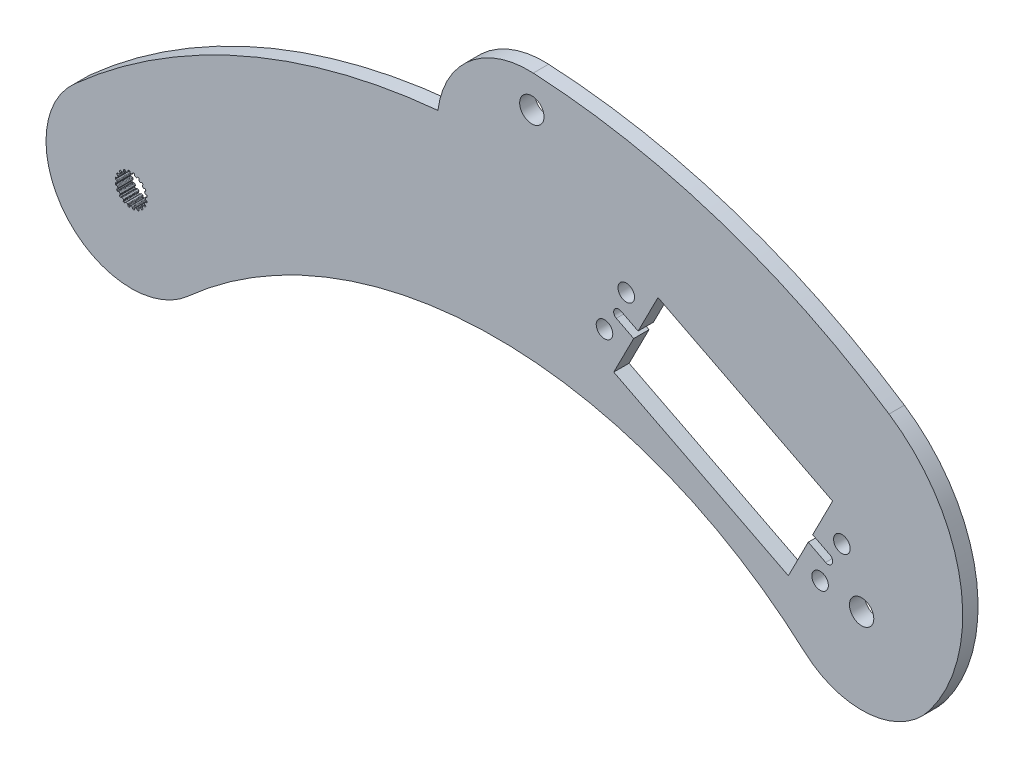
SolidWorks part; units mm, degrees
ref_plane "Front Plane" through (0, 0, 0) normal (0, 0, 1) x (1, 0, 0)
ref_plane "Top Plane" through (0, 0, 0) normal (0, 1, 0) x (1, 0, 0)
ref_plane "Right Plane" through (0, 0, 0) normal (1, 0, 0) x (0, 0, -1)
sketch "Sketch1" plane through (0, 0, 0) normal (0, 0, 1) x (1, 0, 0)
  line L0 (-0.1069, 2.9699) -> (0.1069, 2.9699)
  line L1 (0.3159, 3.2375) -> (0.2537, 3.0575)
  line L2 (-0.2964, 3.2367) -> (-0.2318, 3.0575)
  line L3 (-0.2964, 3.2367) -> (0.3159, 3.2375) construction
  line L4 (0, 3.3252) -> (0, 0) construction
  line L5 (-0.2318, 3.0575) -> (0.2537, 3.0575) construction
  line L6 (-0.4281, 3.3241) -> (0.4281, 3.3263) construction
  line L7 (0.7183, 3.1698) -> (0.7244, 2.9795)
  line L8 (0.816, 2.8576) -> (1.0195, 2.7915)
  line L9 (1.3009, 2.9815) -> (1.1862, 2.8295)
  line L10 (1.6627, 2.7927) -> (1.6097, 2.6099)
  line L11 (1.6591, 2.4655) -> (1.8322, 2.3398)
  line L12 (2.1585, 2.4335) -> (2.0025, 2.3245)
  line L13 (2.4443, 2.1423) -> (2.3374, 1.9847)
  line L14 (2.3398, 1.8322) -> (2.4655, 1.6591)
  line L15 (2.8049, 1.6474) -> (2.6228, 1.5919)
  line L16 (2.9866, 1.2821) -> (2.8363, 1.1653)
  line L17 (2.7915, 1.0195) -> (2.8576, 0.816)
  line L18 (3.1767, 0.7) -> (2.9863, 0.7035)
  line L19 (3.2367, 0.2964) -> (3.0575, 0.2318)
  line L20 (2.9699, 0.1069) -> (2.9699, -0.1069)
  line L21 (3.2375, -0.3159) -> (3.0575, -0.2537)
  line L22 (3.1698, -0.7183) -> (2.9795, -0.7244)
  line L23 (2.8576, -0.816) -> (2.7915, -1.0195)
  line L24 (2.9815, -1.3009) -> (2.8295, -1.1862)
  line L25 (2.7927, -1.6627) -> (2.6099, -1.6097)
  line L26 (2.4655, -1.6591) -> (2.3398, -1.8322)
  line L27 (2.4335, -2.1585) -> (2.3245, -2.0025)
  line L28 (2.1423, -2.4443) -> (1.9847, -2.3374)
  line L29 (1.8322, -2.3398) -> (1.6591, -2.4655)
  line L30 (1.6474, -2.8049) -> (1.5919, -2.6228)
  line L31 (1.2821, -2.9866) -> (1.1653, -2.8363)
  line L32 (1.0195, -2.7915) -> (0.816, -2.8576)
  line L33 (0.7, -3.1767) -> (0.7035, -2.9863)
  line L34 (0.2964, -3.2367) -> (0.2318, -3.0575)
  line L35 (0.1069, -2.9699) -> (-0.1069, -2.9699)
  line L36 (-0.3159, -3.2375) -> (-0.2537, -3.0575)
  line L37 (-0.7183, -3.1698) -> (-0.7244, -2.9795)
  line L38 (-0.816, -2.8576) -> (-1.0195, -2.7915)
  line L39 (-1.3009, -2.9815) -> (-1.1862, -2.8295)
  line L40 (-1.6627, -2.7927) -> (-1.6097, -2.6099)
  line L41 (-1.6591, -2.4655) -> (-1.8322, -2.3398)
  line L42 (-2.1585, -2.4335) -> (-2.0025, -2.3245)
  line L43 (-2.4443, -2.1423) -> (-2.3374, -1.9847)
  line L44 (-2.3398, -1.8322) -> (-2.4655, -1.6591)
  line L45 (-2.8049, -1.6474) -> (-2.6228, -1.5919)
  line L46 (-2.9866, -1.2821) -> (-2.8363, -1.1653)
  line L47 (-2.7915, -1.0195) -> (-2.8576, -0.816)
  line L48 (-3.1767, -0.7) -> (-2.9863, -0.7035)
  line L49 (-3.2367, -0.2964) -> (-3.0575, -0.2318)
  line L50 (-2.9699, -0.1069) -> (-2.9699, 0.1069)
  line L51 (-3.2375, 0.3159) -> (-3.0575, 0.2537)
  line L52 (-3.1698, 0.7183) -> (-2.9795, 0.7244)
  line L53 (-2.8576, 0.816) -> (-2.7915, 1.0195)
  line L54 (-2.9815, 1.3009) -> (-2.8295, 1.1862)
  line L55 (-2.7927, 1.6627) -> (-2.6099, 1.6097)
  line L56 (-2.4655, 1.6591) -> (-2.3398, 1.8322)
  line L57 (-2.4335, 2.1585) -> (-2.3245, 2.0025)
  line L58 (-2.1423, 2.4443) -> (-1.9847, 2.3374)
  line L59 (-1.8322, 2.3398) -> (-1.6591, 2.4655)
  line L60 (-1.6474, 2.8049) -> (-1.5919, 2.6228)
  line L61 (-1.2821, 2.9866) -> (-1.1653, 2.8363)
  line L62 (-1.0195, 2.7915) -> (-0.816, 2.8576)
  line L63 (-0.7, 3.1767) -> (-0.7035, 2.9863)
  line L64 (0.4281, 3.3263) -> (0.62, 3.2938)
  line L65 (1.4351, 3.0312) -> (1.6075, 2.9409)
  line L66 (2.3015, 2.4394) -> (2.4376, 2.3003)
  line L67 (2.9427, 1.6088) -> (3.0291, 1.4344)
  line L68 (3.2958, 0.6207) -> (3.3241, 0.4281)
  line L69 (3.3263, -0.4281) -> (3.2938, -0.62)
  line L70 (3.0312, -1.4351) -> (2.9409, -1.6075)
  line L71 (2.4394, -2.3015) -> (2.3003, -2.4376)
  line L72 (1.6088, -2.9427) -> (1.4344, -3.0291)
  line L73 (0.6207, -3.2958) -> (0.4281, -3.3241)
  line L74 (-0.4281, -3.3263) -> (-0.62, -3.2938)
  line L75 (-1.4351, -3.0312) -> (-1.6075, -2.9409)
  line L76 (-2.3015, -2.4394) -> (-2.4376, -2.3003)
  line L77 (-2.9427, -1.6088) -> (-3.0291, -1.4344)
  line L78 (-3.2958, -0.6207) -> (-3.3241, -0.4281)
  line L79 (-3.3263, 0.4281) -> (-3.2938, 0.62)
  line L80 (-3.0312, 1.4351) -> (-2.9409, 1.6075)
  line L81 (-2.4394, 2.3015) -> (-2.3003, 2.4376)
  line L82 (-1.6088, 2.9427) -> (-1.4344, 3.0291)
  line L83 (-0.6207, 3.2958) -> (-0.4281, 3.3241)
  line L84 (-11.8753, 13.2369) -> (11.8753, -13.2369) construction
  line L85 (164.2753, 13.2369) -> (140.5247, -13.2369) construction
  line L86 (0, 0) -> (152.4, 0) construction
  arc A0 (0.2537, 3.0575) -> (0.1069, 2.9699) centre (0.1283, 3.1009) cw
  arc A1 (-0.2318, 3.0575) -> (-0.1069, 2.9699) centre (-0.1069, 3.1026) ccw
  arc A2 (0.62, 3.2938) -> (0.7183, 3.1698) centre (0.5856, 3.1656) cw
  arc A3 (0.7244, 2.9795) -> (0.816, 2.8576) centre (0.857, 2.9838) ccw
  arc A4 (-0.4281, 3.3241) -> (-0.2964, 3.2367) centre (-0.4213, 3.1916) cw
  arc A5 (0.4281, 3.3263) -> (0.3159, 3.2375) centre (0.4413, 3.1942) ccw
  arc A6 (1.1862, 2.8295) -> (1.0195, 2.7915) centre (1.0802, 2.9095) cw
  arc A7 (1.4351, 3.0312) -> (1.3009, 2.9815) centre (1.4068, 2.9015) ccw
  arc A8 (1.6075, 2.9409) -> (1.6627, 2.7927) centre (1.5352, 2.8297) cw
  arc A9 (1.6097, 2.6099) -> (1.6591, 2.4655) centre (1.7371, 2.5729) ccw
  arc A10 (2.0025, 2.3245) -> (1.8322, 2.3398) centre (1.9264, 2.4332) cw
  arc A11 (2.3015, 2.4394) -> (2.1585, 2.4335) centre (2.2346, 2.3248) ccw
  arc A12 (2.4376, 2.3003) -> (2.4443, 2.1423) centre (2.3345, 2.2168) cw
  arc A13 (2.3374, 1.9847) -> (2.3398, 1.8322) centre (2.4472, 1.9102) ccw
  arc A14 (2.6228, 1.5919) -> (2.4655, 1.6591) centre (2.5841, 1.7189) cw
  arc A15 (2.9427, 1.6088) -> (2.8049, 1.6474) centre (2.8436, 1.5205) ccw
  arc A16 (3.0291, 1.4344) -> (2.9866, 1.2821) centre (2.9052, 1.3869) cw
  arc A17 (2.8363, 1.1653) -> (2.7915, 1.0195) centre (2.9177, 1.0605) ccw
  arc A18 (2.9863, 0.7035) -> (2.8576, 0.816) centre (2.9887, 0.8362) cw
  arc A19 (3.2958, 0.6207) -> (3.1767, 0.7) centre (3.1743, 0.5673) ccw
  arc A20 (3.3241, 0.4281) -> (3.2367, 0.2964) centre (3.1916, 0.4213) cw
  arc A21 (3.0575, 0.2318) -> (2.9699, 0.1069) centre (3.1026, 0.1069) ccw
  arc A22 (3.0575, -0.2537) -> (2.9699, -0.1069) centre (3.1009, -0.1283) cw
  arc A23 (3.3263, -0.4281) -> (3.2375, -0.3159) centre (3.1942, -0.4413) ccw
  arc A24 (3.2938, -0.62) -> (3.1698, -0.7183) centre (3.1656, -0.5856) cw
  arc A25 (2.9795, -0.7244) -> (2.8576, -0.816) centre (2.9838, -0.857) ccw
  arc A26 (2.8295, -1.1862) -> (2.7915, -1.0195) centre (2.9095, -1.0802) cw
  arc A27 (3.0312, -1.4351) -> (2.9815, -1.3009) centre (2.9015, -1.4068) ccw
  arc A28 (2.9409, -1.6075) -> (2.7927, -1.6627) centre (2.8297, -1.5352) cw
  arc A29 (2.6099, -1.6097) -> (2.4655, -1.6591) centre (2.5729, -1.7371) ccw
  arc A30 (2.3245, -2.0025) -> (2.3398, -1.8322) centre (2.4332, -1.9264) cw
  arc A31 (2.4394, -2.3015) -> (2.4335, -2.1585) centre (2.3248, -2.2346) ccw
  arc A32 (2.3003, -2.4376) -> (2.1423, -2.4443) centre (2.2168, -2.3345) cw
  arc A33 (1.9847, -2.3374) -> (1.8322, -2.3398) centre (1.9102, -2.4472) ccw
  arc A34 (1.5919, -2.6228) -> (1.6591, -2.4655) centre (1.7189, -2.5841) cw
  arc A35 (1.6088, -2.9427) -> (1.6474, -2.8049) centre (1.5205, -2.8436) ccw
  arc A36 (1.4344, -3.0291) -> (1.2821, -2.9866) centre (1.3869, -2.9052) cw
  arc A37 (1.1653, -2.8363) -> (1.0195, -2.7915) centre (1.0605, -2.9177) ccw
  arc A38 (0.7035, -2.9863) -> (0.816, -2.8576) centre (0.8362, -2.9887) cw
  arc A39 (0.6207, -3.2958) -> (0.7, -3.1767) centre (0.5673, -3.1743) ccw
  arc A40 (0.4281, -3.3241) -> (0.2964, -3.2367) centre (0.4213, -3.1916) cw
  arc A41 (0.2318, -3.0575) -> (0.1069, -2.9699) centre (0.1069, -3.1026) ccw
  arc A42 (-0.2537, -3.0575) -> (-0.1069, -2.9699) centre (-0.1283, -3.1009) cw
  arc A43 (-0.4281, -3.3263) -> (-0.3159, -3.2375) centre (-0.4413, -3.1942) ccw
  arc A44 (-0.62, -3.2938) -> (-0.7183, -3.1698) centre (-0.5856, -3.1656) cw
  arc A45 (-0.7244, -2.9795) -> (-0.816, -2.8576) centre (-0.857, -2.9838) ccw
  arc A46 (-1.1862, -2.8295) -> (-1.0195, -2.7915) centre (-1.0802, -2.9095) cw
  arc A47 (-1.4351, -3.0312) -> (-1.3009, -2.9815) centre (-1.4068, -2.9015) ccw
  arc A48 (-1.6075, -2.9409) -> (-1.6627, -2.7927) centre (-1.5352, -2.8297) cw
  arc A49 (-1.6097, -2.6099) -> (-1.6591, -2.4655) centre (-1.7371, -2.5729) ccw
  arc A50 (-2.0025, -2.3245) -> (-1.8322, -2.3398) centre (-1.9264, -2.4332) cw
  arc A51 (-2.3015, -2.4394) -> (-2.1585, -2.4335) centre (-2.2346, -2.3248) ccw
  arc A52 (-2.4376, -2.3003) -> (-2.4443, -2.1423) centre (-2.3345, -2.2168) cw
  arc A53 (-2.3374, -1.9847) -> (-2.3398, -1.8322) centre (-2.4472, -1.9102) ccw
  arc A54 (-2.6228, -1.5919) -> (-2.4655, -1.6591) centre (-2.5841, -1.7189) cw
  arc A55 (-2.9427, -1.6088) -> (-2.8049, -1.6474) centre (-2.8436, -1.5205) ccw
  arc A56 (-3.0291, -1.4344) -> (-2.9866, -1.2821) centre (-2.9052, -1.3869) cw
  arc A57 (-2.8363, -1.1653) -> (-2.7915, -1.0195) centre (-2.9177, -1.0605) ccw
  arc A58 (-2.9863, -0.7035) -> (-2.8576, -0.816) centre (-2.9887, -0.8362) cw
  arc A59 (-3.2958, -0.6207) -> (-3.1767, -0.7) centre (-3.1743, -0.5673) ccw
  arc A60 (-3.3241, -0.4281) -> (-3.2367, -0.2964) centre (-3.1916, -0.4213) cw
  arc A61 (-3.0575, -0.2318) -> (-2.9699, -0.1069) centre (-3.1026, -0.1069) ccw
  arc A62 (-3.0575, 0.2537) -> (-2.9699, 0.1069) centre (-3.1009, 0.1283) cw
  arc A63 (-3.3263, 0.4281) -> (-3.2375, 0.3159) centre (-3.1942, 0.4413) ccw
  arc A64 (-3.2938, 0.62) -> (-3.1698, 0.7183) centre (-3.1656, 0.5856) cw
  arc A65 (-2.9795, 0.7244) -> (-2.8576, 0.816) centre (-2.9838, 0.857) ccw
  arc A66 (-2.8295, 1.1862) -> (-2.7915, 1.0195) centre (-2.9095, 1.0802) cw
  arc A67 (-3.0312, 1.4351) -> (-2.9815, 1.3009) centre (-2.9015, 1.4068) ccw
  arc A68 (-2.9409, 1.6075) -> (-2.7927, 1.6627) centre (-2.8297, 1.5352) cw
  arc A69 (-2.6099, 1.6097) -> (-2.4655, 1.6591) centre (-2.5729, 1.7371) ccw
  arc A70 (-2.3245, 2.0025) -> (-2.3398, 1.8322) centre (-2.4332, 1.9264) cw
  arc A71 (-2.4394, 2.3015) -> (-2.4335, 2.1585) centre (-2.3248, 2.2346) ccw
  arc A72 (-2.3003, 2.4376) -> (-2.1423, 2.4443) centre (-2.2168, 2.3345) cw
  arc A73 (-1.9847, 2.3374) -> (-1.8322, 2.3398) centre (-1.9102, 2.4472) ccw
  arc A74 (-1.5919, 2.6228) -> (-1.6591, 2.4655) centre (-1.7189, 2.5841) cw
  arc A75 (-1.6088, 2.9427) -> (-1.6474, 2.8049) centre (-1.5205, 2.8436) ccw
  arc A76 (-1.4344, 3.0291) -> (-1.2821, 2.9866) centre (-1.3869, 2.9052) cw
  arc A77 (-1.1653, 2.8363) -> (-1.0195, 2.7915) centre (-1.0605, 2.9177) ccw
  arc A78 (-0.7035, 2.9863) -> (-0.816, 2.8576) centre (-0.8362, 2.9887) cw
  arc A79 (-0.6207, 3.2958) -> (-0.7, 3.1767) centre (-0.5673, 3.1743) ccw
  circle A80 centre (0, 0) radius 12.7 construction
  arc A81 (-11.8753, 13.2369) -> (164.2753, 13.2369) centre (76.2, -84.9368) cw
  arc A82 (11.8753, -13.2369) -> (140.5247, -13.2369) centre (76.2, -84.9368) cw
  arc A84 (-11.8753, 13.2369) -> (11.8753, -13.2369) centre (0, 0) ccw
  arc A85 (164.2753, 13.2369) -> (140.5247, -13.2369) centre (152.4, 0) cw
  point P14 (0, 2.9699)
  point P26 (0, 0)
  point P247 (0, 0)
  dimension "D4" = 0.1327
  dimension "D8" = 20
  dimension "D9" = 25.4
  dimension "D10" = 131.8914
  dimension "D1" = 2.9699
  dimension "D2" = 0.2139
  dimension "D3" = 0.1904
  dimension "D5" = 0.0877
  dimension "D6" = 0.4855
  dimension "D7" = 0.8563
  dimension "D11" = 35.5662
  dimension "D12" = 152.4
extrude "Boss-Extrude1" add sketch "Sketch1" along normal blind 3.2004
sketch "Sketch2" plane through (0, 0, 3.2004) normal (0, 0, 1) x (1, 0, 0)
  line L0 (132.2879, 12.7254) -> (132.9641, 14.0508) construction
  line L5 (128.1311, 26.252) -> (118.8966, 8.1515) construction
  line L7 (109.9175, 35.5442) -> (146.3447, 16.9598)
  line L13 (109.9175, 35.5442) -> (100.683, 17.4437)
  line L19 (98.7496, 24.2228) -> (103.2942, 33.1305) construction
  line L20 (143.7335, 1.273) -> (148.2781, 10.1807) construction
  line L24 (101.0219, 28.6767) -> (146.0058, 5.7268) construction
  line L30 (100.683, 17.4437) -> (137.1102, -1.1407)
  line L31 (146.3447, 16.9598) -> (137.1102, -1.1407)
  circle A7 centre (103.2942, 33.1305) radius 1.7272
  circle A9 centre (143.7335, 1.273) radius 1.7272
  circle A10 centre (148.2781, 10.1807) radius 1.7272
  circle A11 centre (98.7496, 24.2228) radius 1.7272
  circle A13 centre (132.2879, 12.7254) radius 3.429 construction
  arc A14 (0, 0) -> (152.4, 0) centre (76.2, -84.9368) cw construction
  arc A15 (-11.8753, 13.2369) -> (11.8753, -13.2369) centre (0, 0) ccw construction
  arc A16 (140.5247, -13.2369) -> (164.2753, 13.2369) centre (152.4, 0) ccw construction
  arc A17 (164.2753, 13.2369) -> (-11.8753, 13.2369) centre (76.2, -84.9368) ccw construction
  circle A18 centre (152.4, 0) radius 2.54
  point P0 (132.2879, 12.7254)
  point P1 (99.9946, 26.663)
  point P24 (123.5139, 17.2018)
  dimension "D2" = 15.4
  dimension "D3" = 6.858
  dimension "D5" = 3.4544
  dimension "D10" = 5.08
  dimension "D6" = 2.2606
  dimension "D8" = 20.32
  dimension "D13" = 23.7998
  dimension "D1" = 50.5
  dimension "D4" = 10
  dimension "D7" = 1.4879
  dimension "D9" = 40.894
extrude "Cut-Extrude1" cut sketch "Sketch2" against normal up to surface (3.2004 mm away) up to face at (76.2, 8.6481, 0)
sketch "Sketch3" plane through (0, 0, 3.2004) normal (0, 0, 1) x (1, 0, 0)
  line L0 (146.3447, 16.9598) -> (137.1102, -1.1407) construction
  line L1 (109.9175, 35.5442) -> (100.683, 17.4437) construction
  line L4 (102.1419, 29.2459) -> (105.762, 27.399)
  line L5 (102.1419, 29.2459) -> (101.2184, 27.4358) construction
  line L7 (101.2184, 27.4358) -> (104.8385, 25.5889)
  line L8 (105.762, 27.399) -> (104.8385, 25.5889)
  line L9 (142.1892, 8.8146) -> (145.8093, 6.9677)
  line L10 (142.1892, 8.8146) -> (141.2657, 7.0045)
  line L11 (141.2657, 7.0045) -> (144.8858, 5.1576)
  line L12 (145.8093, 6.9677) -> (144.8858, 5.1576) construction
  arc A6 (145.8093, 6.9677) -> (144.8858, 5.1576) centre (145.3475, 6.0627) cw
  arc A7 (102.1419, 29.2459) -> (101.2184, 27.4358) centre (101.6802, 28.3409) ccw
  point P22 (105.3003, 26.494)
  point P23 (141.7274, 7.9096)
  dimension "D4" = 4.064
  dimension "D5" = 2.032
extrude "Cut-Extrude2" cut sketch "Sketch3" against normal up to surface (3.2004 mm away) up to face at (97.0224, 24.2228, 0)
sketch "Sketch4" plane through (0, 0, 3.2004) normal (0, 0, 1) x (1, 0, 0)
  line L1 (83.5881, 56.2861) -> (152.4, 0) construction
  line L2 (83.5881, 56.2861) -> (83.1655, 46.7705) construction
  line L4 (158.1231, 38.5869) -> (166.6312, -10.6636) construction
  line L5 (83.89, 63.0847) -> (63.9945, 46.3886) construction
  arc A0 (63.9945, 46.3886) -> (83.89, 63.0847) centre (82.9016, 44.0604) cw
  arc A1 (164.2753, 13.2369) -> (-11.8753, 13.2369) centre (76.2, -84.9368) ccw construction
  circle A3 centre (152.4, 0) radius 2.54 construction
  circle A4 centre (83.5881, 56.2861) radius 2.54
  circle A5 centre (152.4, 0) radius 2.54 construction
  arc A6 (83.89, 63.0847) -> (158.1231, 38.5869) centre (76.2, -84.9368) cw
  arc A7 (166.6312, -10.6636) -> (164.2753, 13.2369) centre (152.4, 0) ccw
  arc A8 (164.2753, 13.2369) -> (63.9945, 46.3886) centre (76.2, -84.9368) ccw
  arc A9 (164.2753, 13.2369) -> (-11.8753, 13.2369) centre (76.2, -84.9368) ccw construction
  arc A10 (158.1231, 38.5869) -> (166.6312, -10.6636) centre (139.1275, 9.9453) cw
  arc A11 (140.5247, -13.2369) -> (164.2753, 13.2369) centre (152.4, 0) ccw construction
  point P3 (82.7663, 37.7814)
  dimension "D4" = 49.98
  dimension "D3" = 19.05
  dimension "D1" = 9.525
  dimension "D2" = 88.9
  dimension "D5" = 25.9729
extrude "Boss-Extrude2" add sketch "Sketch4" against normal up to surface (3.2004 mm away) up to face at (123.5139, 17.2018, 0)
